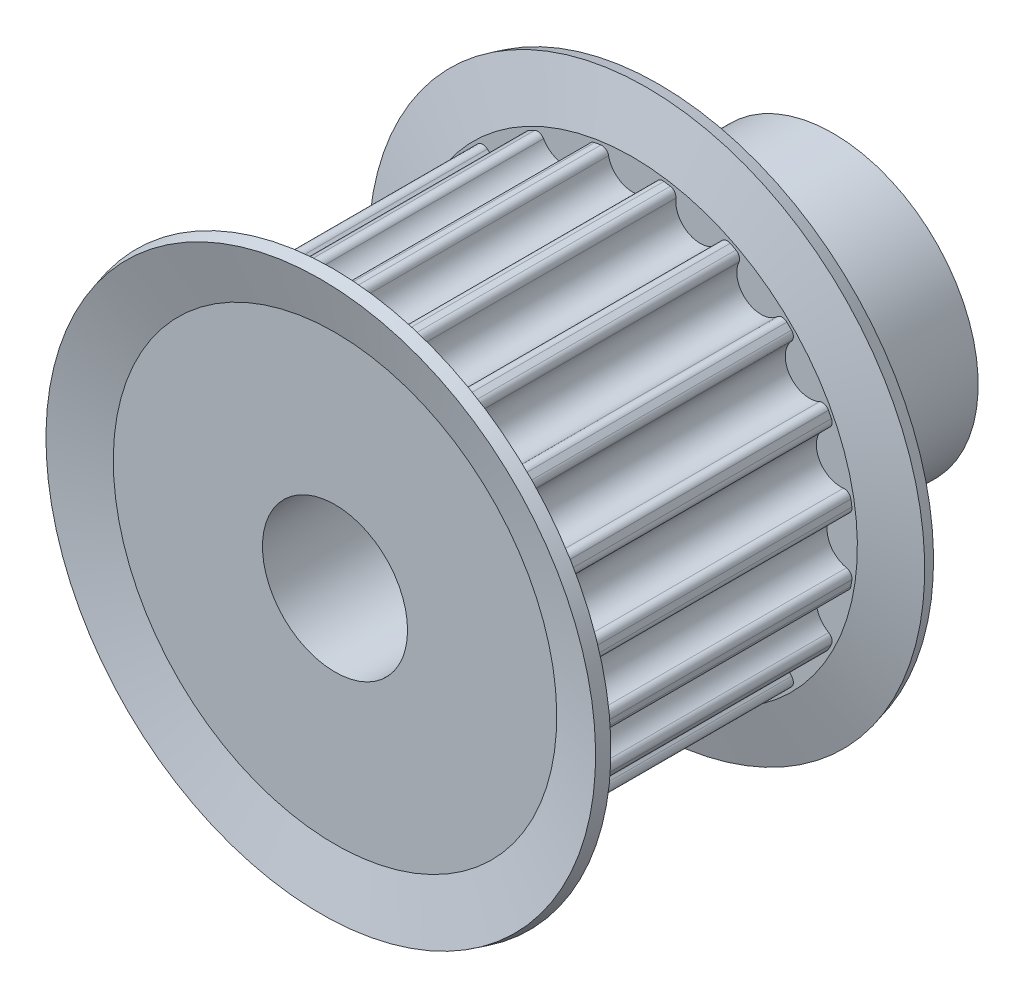
SolidWorks part; units mm, degrees
ref_plane "Front" through (0, 0, 0) normal (0, 0, 1) x (1, 0, 0)
ref_plane "Top" through (0, 0, 0) normal (0, 1, 0) x (1, 0, 0)
ref_plane "Right" through (0, 0, 0) normal (1, 0, 0) x (0, 0, -1)
sketch "Ritning 1" plane through (0, 0, 0) normal (1, 0, 0) x (0, 0, -1)
  line L0 (6.4, 4.585) -> (6.4, 1.415)
  line L1 (-6.4, 4.585) -> (6.4, 4.585)
  line L2 (-6.4, 4.585) -> (-6.4, -4.585)
  line L3 (-6.4, -4.585) -> (6.4, -4.585) construction
  line L4 (-6.4, -4.585) -> (6.4, -4.585)
  line L5 (14.2, 1.415) -> (14.2, -4.585)
  line L6 (6.4, 1.415) -> (14.2, 1.415)
  line L7 (14.2, -4.585) -> (6.4, -4.585) construction
  line L9 (14.2, -4.585) -> (6.4, -4.585)
  dimension "D1" = 6.4
  dimension "D2" = 14.2
  dimension "D3" = 6.4
  dimension "D4" = 1.415
  dimension "D5" = 4.585
  dimension "D6" = 4.585
revolve "Kugghjulsämne" add sketch "Ritning 1" angle 360 about L9
sketch "Ritning 2" plane through (0, 0, 6.4) normal (0, 0, 1) x (1, 0, 0)
  line L0 (0, 3.465) -> (0, -4.585) construction
  line L1 (1.3025, 4.492) -> (1.3025, 5.612)
  line L2 (1.3025, 5.612) -> (-1.3025, 5.612)
  line L3 (-1.3025, 5.612) -> (-1.3025, 4.492)
  arc A0 (1.3025, 4.492) -> (0.9856, 4.2691) centre (1.2624, 4.2123) ccw
  arc A1 (-0.9856, 4.2691) -> (-1.3025, 4.492) centre (-1.2624, 4.2123) ccw
  arc A2 (-0.9856, 4.2691) -> (0.9856, 4.2691) centre (0, 4.471) ccw
  circle A3 centre (0, -4.585) radius 9.17 construction
  dimension "D1" = 0.2826
  dimension "D2" = 1.006
  dimension "D3" = 0.9856
  dimension "D4" = 1.3025
  dimension "D5" = 8.7973
  dimension "D6" = 10.197
extrude "Kugglucka" cut sketch "Ritning 2" against normal up to surface (12.8 mm away) up to face at (0, 4.585, -6.4)
pattern_circular "CirPattern" count 20 over 360 about axis through (0, -4.585, 0) along (0, 0, 1) of "Kugglucka"
sketch "Ritning 3" plane through (0, 0, 0) normal (1, 0, 0) x (0, 0, -1)
  line L1 (-5.9, 3.0625) -> (-6.4, 3.0625)
  line L2 (-5.9, 4.719) -> (-5.9, 3.0625)
  line L3 (-6.9884, 6.781) -> (-6.4884, 6.915)
  line L4 (-6.4, 4.585) -> (-6.9884, 6.781)
  line L5 (-6.4, 3.0625) -> (-6.4, 4.585)
  line L6 (-5.9, 4.719) -> (-6.4884, 6.915)
  line L7 (6.4, -4.585) -> (-6.4, -4.585) construction
  line L9 (5.9, 3.0625) -> (6.4, 3.0625)
  line L10 (5.9, 4.719) -> (5.9, 3.0625)
  line L11 (6.9884, 6.781) -> (6.4884, 6.915)
  line L12 (6.4, 4.585) -> (6.9884, 6.781)
  line L13 (6.4, 3.0625) -> (6.4, 4.585)
  line L14 (5.9, 4.719) -> (6.4884, 6.915)
  dimension "D1" = 4.585
revolve "Flänsar" add sketch "Ritning 3" angle 360 about L7
sketch "Ritning 4" plane through (0, 0, 6.4) normal (0, 0, 1) x (1, 0, 0)
  circle A0 centre (0, -4.585) radius 3
  circle A1 centre (0, -4.585) radius 9.17 construction
  dimension "D1" = 6
extrude "Axelhål" cut sketch "Ritning 4" against normal through all
